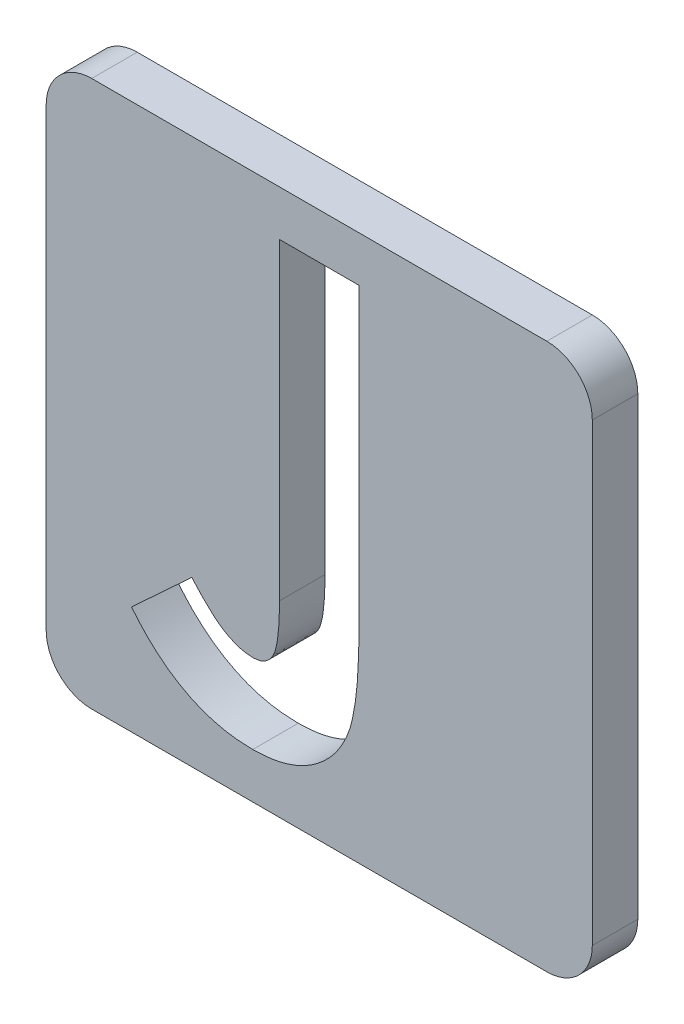
SolidWorks part; units mm, degrees
ref_plane "Front Plane" through (0, 0, 0) normal (0, 0, 1) x (1, 0, 0)
ref_plane "Top Plane" through (0, 0, 0) normal (0, 1, 0) x (1, 0, 0)
ref_plane "Right Plane" through (0, 0, 0) normal (1, 0, 0) x (0, 0, -1)
sketch "Sketch1" plane through (0, 0, 0) normal (0, 0, 1) x (1, 0, 0)
  line L1 (-50, 60) -> (50, 60)
  line L2 (-60, 50) -> (-60, -50)
  line L3 (-50, -60) -> (50, -60)
  line L4 (60, 50) -> (60, -50)
  line L5 (-60, 60) -> (60, -60) construction
  line L6 (-60, -60) -> (60, 60) construction
  arc A0 (-60, -50) -> (-50, -60) centre (-50, -50) ccw
  arc A1 (50, -60) -> (60, -50) centre (50, -50) ccw
  arc A2 (50, 60) -> (60, 50) centre (50, 50) cw
  arc A3 (-50, 60) -> (-60, 50) centre (-50, 50) ccw
  point P0 (0, 0)
  dimension "D3" = 10
  dimension "D1" = 120
  dimension "D2" = 120
extrude "Boss-Extrude1" add sketch "Sketch1" along normal blind 10 contours A3 L2 A0 L3 A1 L4 A2 L1
sketch "Sketch2" plane through (0, 0, 10) normal (0, 0, 1) x (1, 0, 0)
  line L0 (0, 0) -> (0, 40) construction
  line L1 (-50, 50) -> (50, 50) construction
  line L2 (-50, 50) -> (-50, -50) construction
  line L3 (-50, -50) -> (50, -50) construction
  line L4 (50, 50) -> (50, -50) construction
  line L5 (-50, 50) -> (50, -50) construction
  line L6 (-50, -50) -> (50, 50) construction
  line L7 (0, 40) -> (-40, 40) construction
  line L8 (-40, 40) -> (-40, 0) construction
  line L9 (-40, 0) -> (0, 0) construction
  line L11 (0, 20) -> (-20, 20) construction
  line L12 (-20, 40) -> (-20, 20) construction
  circle A0 centre (0, 40) radius 4 construction
  circle A1 centre (0, 20) radius 4 construction
  circle A2 centre (0, 0) radius 4 construction
  circle A3 centre (-20, 20) radius 4 construction
  circle A4 centre (-20, 40) radius 4 construction
  circle A5 centre (-40, 40) radius 4 construction
  circle A6 centre (0, 0) radius 4 construction
  circle A7 centre (20, 0) radius 4 construction
  circle A8 centre (40, 0) radius 4 construction
  circle A9 centre (40, 20) radius 4 construction
  circle A10 centre (40, 40) radius 4 construction
  circle A11 centre (20, 20) radius 4 construction
  circle A12 centre (0, 0) radius 4 construction
  circle A13 centre (0, -20) radius 4 construction
  circle A14 centre (0, -40) radius 4 construction
  circle A15 centre (20, -40) radius 4 construction
  circle A16 centre (40, -40) radius 4 construction
  circle A17 centre (20, -20) radius 4 construction
  circle A18 centre (0, 0) radius 4 construction
  circle A19 centre (-20, 0) radius 4 construction
  circle A20 centre (-40, 0) radius 4 construction
  circle A21 centre (-40, -20) radius 4 construction
  circle A22 centre (-40, -40) radius 4 construction
  circle A23 centre (-20, -20) radius 4 construction
  text T0 "J" font "Century Gothic" height 97.5
  point P0 (0, 0)
  point P55 (0, 0)
  dimension "D4" = 8
  dimension "D1" = 100
  dimension "D2" = 100
  dimension "D3" = 40
  dimension "D5" = 4
extrude "Cut-Extrude23" cut sketch "Sketch2" against normal blind 10
